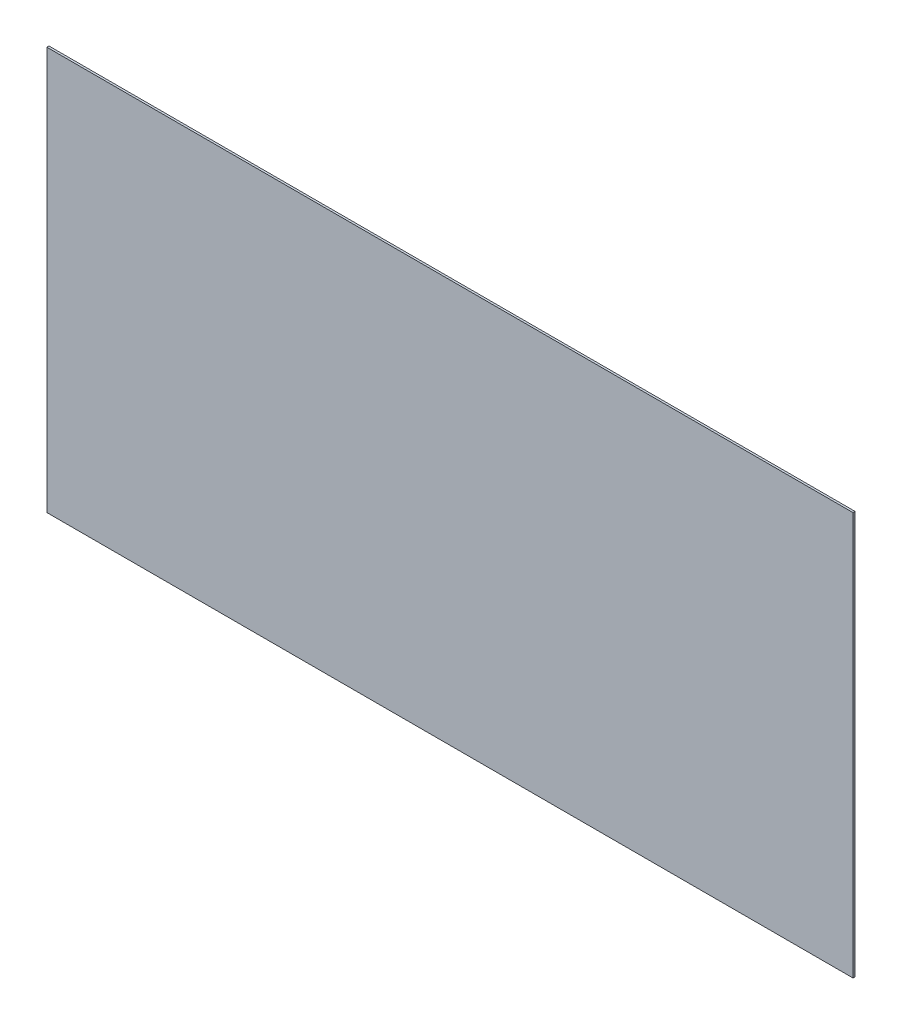
SolidWorks part; units mm, degrees
ref_plane "Front Plane" through (0, 0, 0) normal (0, 0, 1) x (1, 0, 0)
ref_plane "Top Plane" through (0, 0, 0) normal (0, 1, 0) x (1, 0, 0)
ref_plane "Right Plane" through (0, 0, 0) normal (1, 0, 0) x (0, 0, -1)
sketch "Sketch1" plane through (0, 0, 0) normal (0, 0, 1) x (1, 0, 0)
  line L1 (-609.6, 304.8) -> (609.6, 304.8)
  line L2 (-609.6, 304.8) -> (-609.6, -304.8)
  line L3 (-609.6, -304.8) -> (609.6, -304.8)
  line L4 (609.6, 304.8) -> (609.6, -304.8)
  line L5 (-609.6, 304.8) -> (609.6, -304.8) construction
  line L6 (-609.6, -304.8) -> (609.6, 304.8) construction
  point P0 (0, 0)
  dimension "D1" = 1219.2
  dimension "D2" = 609.6
extrude "Boss-Extrude1" add sketch "Sketch1" along normal blind 3.175
